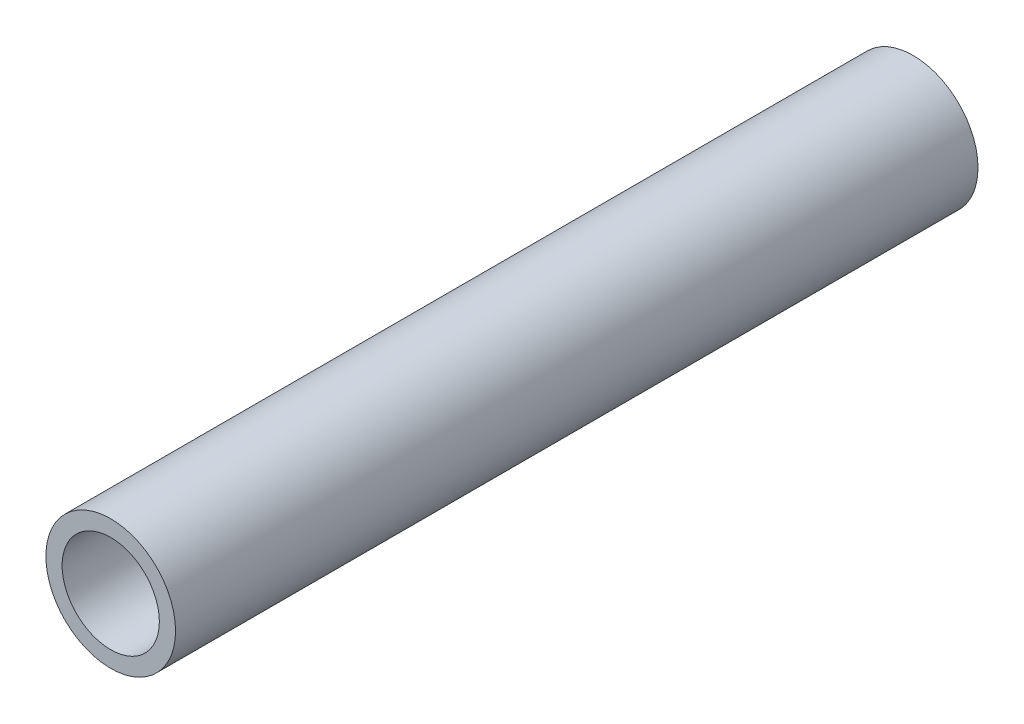
SolidWorks part; units mm, degrees
material "1060 Alloy"
ref_plane "Front Plane" through (0, 0, 0) normal (0, 0, 1) x (1, 0, 0)
ref_plane "Top Plane" through (0, 0, 0) normal (0, 1, 0) x (1, 0, 0)
ref_plane "Right Plane" through (0, 0, 0) normal (1, 0, 0) x (0, 0, -1)
sketch "Sketch1" plane through (0, 0, 0) normal (0, 0, 1) x (1, 0, 0)
  circle A0 centre (0, 0) radius 4
  dimension "D1" = 8
extrude "Extrude-Thin1" add sketch "Sketch1" along normal blind 49.5 thin thin type one direction reverse wall 1
